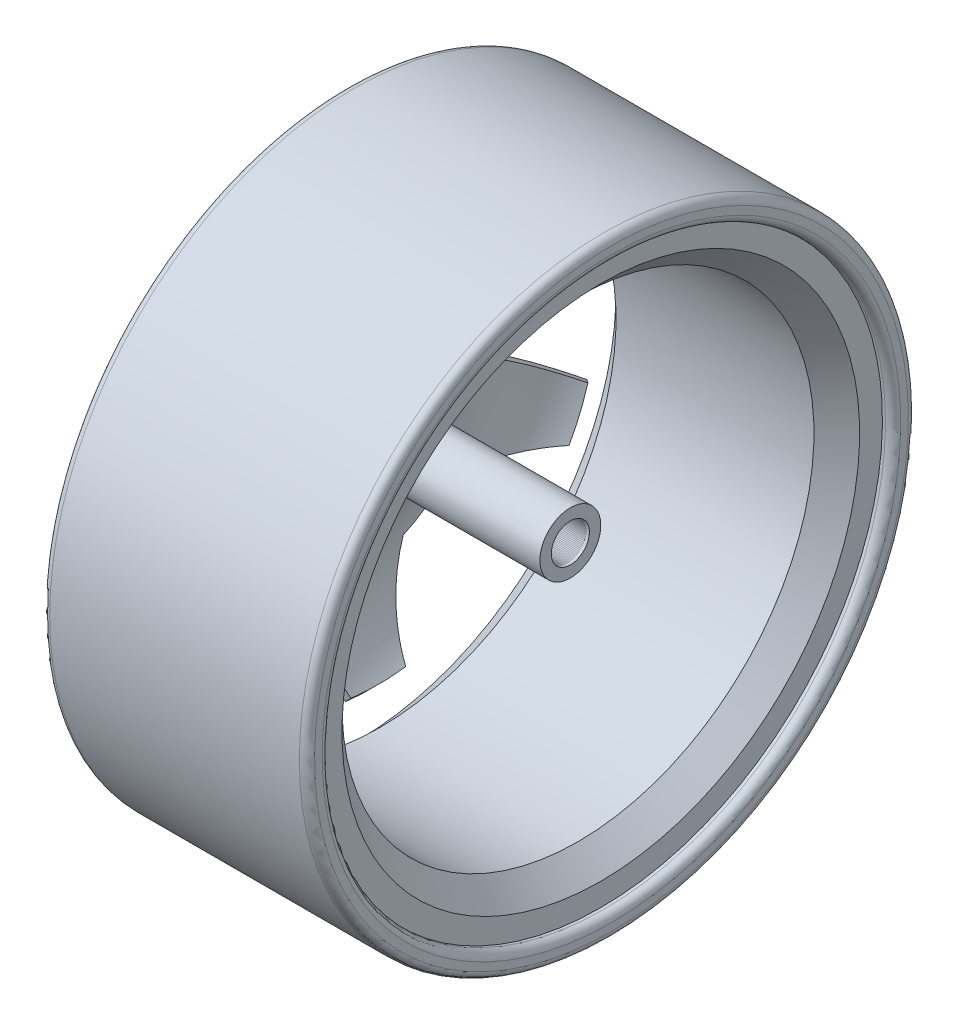
SolidWorks part; units mm, degrees
ref_plane "Front Plane" through (0, 0, 0) normal (0, 0, 1) x (1, 0, 0)
ref_plane "Top Plane" through (0, 0, 0) normal (0, 1, 0) x (1, 0, 0)
ref_plane "Right Plane" through (0, 0, 0) normal (1, 0, 0) x (0, 0, -1)
sketch "Sketch1" plane through (0, 0, 0) normal (0, 0, 1) x (1, 0, 0)
  line L0 (-5, 0) -> (5, 0) construction
  line L1 (0, 0) -> (0, 15.5) construction
  line L2 (-6.5, 15.5) -> (0, 15.5)
  line L3 (0, 15.5) -> (6.5, 15.5)
  line L4 (0, 0) -> (0, 18.5) construction
  line L5 (-6.5, 18.5) -> (6.5, 18.5) construction
  line L6 (0, 16.5) -> (-5, 16.5)
  line L7 (0, 16.5) -> (5, 16.5)
  line L8 (-6.5, 18.5) -> (-8, 18.5)
  line L9 (6.5, 18.5) -> (8, 18.5)
  line L10 (-8, 18.5) -> (-8, 17)
  line L11 (8, 18.5) -> (8, 17)
  line L12 (-6.5, 18.5) -> (-5, 16.5)
  line L13 (-8, 17) -> (-6.5, 15.5)
  line L14 (6.5, 18.5) -> (5, 16.5)
  line L15 (8, 17) -> (6.5, 15.5)
  point P3 (0, 0)
  point P13 (0, 0)
  dimension "D1" = 15.5
  dimension "D2" = 6.5
  dimension "D3" = 18.5
  dimension "D4" = 1
  dimension "D5" = 5
  dimension "D6" = 5
  dimension "D7" = 1.5
  dimension "D8" = 1.5
  dimension "D9" = 1.5
  dimension "D10" = 1.5
  dimension "D11" = 10
revolve "Revolve1" add sketch "Sketch1" angle 360 about L0
sketch "Sketch2" plane through (0, 0, 0) normal (0, 0, 1) x (1, 0, 0)
  line L0 (-6, 2.5) -> (-4.5, 2.5)
  line L1 (-4.5, 2.5) -> (-4.5, 1.25)
  line L2 (-4.5, 1.25) -> (-3.75, 1.25)
  line L3 (-3.75, 1.25) -> (-3.75, 2.5)
  line L4 (-3.75, 2.5) -> (6, 2.5)
  line L5 (-5, 0) -> (5, 0) construction
  line L6 (-6, 2.5) -> (-6, 4.5)
  line L8 (-5.25, 4.5) -> (-5.25, 3.25)
  line L9 (-5.25, 3.25) -> (6, 3.25)
  line L10 (6, 3.25) -> (6, 2.5)
  line L11 (-8, 17) -> (-6.5, 15.5) construction
  line L12 (-6.6086, 15.6086) -> (-7.1389, 16.1389)
  arc A0 (-5.25, 4.5) -> (-6.6086, 15.6086) centre (-0.3145, 10.741) cw
  arc A1 (-6, 4.5) -> (-7.1389, 16.1389) centre (-0.9445, 10.8699) cw
  point P3 (-4.5, 2.5)
  point P5 (-3.75, 2.5)
  dimension "D1" = 12
  dimension "D2" = 1.25
  dimension "D3" = 2.5
  dimension "D4" = 1.5
  dimension "D5" = 0.75
  dimension "D6" = 2
  dimension "D7" = 0.75
  dimension "D8" = 0.75
  dimension "D9" = 0.75
revolve "Revolve2" add sketch "Sketch2" angle 360 about L2
sketch "Sketch6" plane through (0, 0, 0) normal (1, 0, 0) x (0, 0, -1)
  line L0 (0, 1.25) -> (0, 7.8126) construction
  line L1 (8.4749, 13.4916) -> (1.5, 7.6389)
  line L2 (-1.5, 7.6389) -> (-8.4749, 13.4916)
  line L3 (15.4501, -3.891) -> (7.7286, 0.934)
  line L4 (6.8015, 3.7871) -> (10.2123, 12.2292)
  line L5 (1.0738, -15.8963) -> (3.2765, -7.0617)
  line L6 (5.7036, -5.2983) -> (14.7865, -5.9335)
  line L7 (-14.7865, -5.9335) -> (-5.7036, -5.2983)
  line L8 (-3.2765, -7.0617) -> (-1.0738, -15.8963)
  line L9 (-10.2123, 12.2292) -> (-6.8015, 3.7871)
  line L10 (-7.7286, 0.934) -> (-15.4501, -3.891)
  arc A0 (1.2622, -15.1405) -> (14.7865, -5.9335) centre (0, 1.25) ccw
  arc A2 (1.5, 7.6389) -> (-1.5, 7.6389) centre (0, 1.25) ccw
  arc A3 (7.7286, 0.934) -> (6.8015, 3.7871) centre (1.1888, 0.3863) ccw
  arc A4 (3.2765, -7.0617) -> (5.7036, -5.2983) centre (0.7347, -1.0113) ccw
  arc A5 (-5.7036, -5.2983) -> (-3.2765, -7.0617) centre (-0.7347, -1.0113) ccw
  arc A6 (-6.8015, 3.7871) -> (-7.7286, 0.934) centre (-1.1888, 0.3863) ccw
  arc A7 (14.2304, -3.1289) -> (10.17, 12.1244) centre (0, 1.25) ccw
  arc A10 (8.4749, 13.4916) -> (-8.4749, 13.4916) centre (0, 1.25) ccw
  arc A11 (-14.7865, -5.9335) -> (-1.2622, -15.1405) centre (0, 1.25) ccw
  arc A12 (-10.17, 12.1244) -> (-14.2304, -3.1289) centre (0, 1.25) ccw
  point P31 (0, 0)
  dimension "D1" = 3
  dimension "D2" = 50
  dimension "D3" = 50
  dimension "D5" = 5
extrude "Cut-Extrude1" cut sketch "Sketch6" against normal blind 10 and the other way through all contours L1 A10 L2 A2 | L3 A7 L4 A3 | A4 L5 A0 L6 | L7 A11 L8 A5 | L9 A12 L10 A6
sketch "Sketch8" plane through (0, 0, 0) normal (0, 0, 1) x (1, 0, 0)
  line L0 (-8.2, 18.5) -> (-6.5, 18.5)
  line L1 (-6.5, 18.5) -> (-8, 18.5) construction
  line L2 (-6.5, 18.5) -> (-5, 16.5)
  line L3 (-5, 16.5) -> (5, 16.5)
  line L4 (5, 16.5) -> (6.5, 18.5)
  line L5 (6.5, 18.5) -> (8.2, 18.5)
  line L6 (6.5, 18.5) -> (8, 18.5) construction
  line L7 (8.7, 19) -> (8.7, 19.5)
  line L8 (8.2, 20) -> (-8.2, 20)
  line L9 (-8.7, 19.5) -> (-8.7, 19)
  line L10 (-6.5, -18.5) -> (-6.5, 18.5) construction
  arc A0 (8.7, 19.5) -> (8.2, 20) centre (8.2, 19.5) ccw
  arc A1 (8.2, 18.5) -> (8.7, 19) centre (8.2, 19) ccw
  arc A2 (-8.2, 18.5) -> (-8.7, 19) centre (-8.2, 19) cw
  arc A3 (-8.2, 20) -> (-8.7, 19.5) centre (-8.2, 19.5) ccw
  point P5 (0, 20)
  point P24 (8.7, 18.5)
  point P27 (-8.7, 18.5)
  dimension "D3" = 0.5
  dimension "D1" = 20
  dimension "D2" = 2.2
revolve "Revolve3" add sketch "Sketch8" angle 360 about L0
fillet "Fillet1" radius 0.5 3 edges at (-6, 1.25, 1.25) (-4.5, 1.25, 1.25) (-6, 1.25, 3.25)
fillet "Fillet2" radius 0.1 20 edges at (-8.5499, -1.8095, 12.1191) (-7.1389, -4.5, 13.7338) (-8.6561, -5.6053, 10.0937) (-9.0332, -5.8327, 5.1869) (-8.5165, -11.1311, 2.2619) (-7.1389, -13.6389, 0) (-8.6665, -10.6868, -2.3727) (-9.0451, -6.7043, -3.9993) (-8.8314, -5.5565, -9.3962) (-7.1389, -4.5, -13.7338) (-8.9724, -0.9227, -10.6999) (-8.816, 2.0646, -7.5332) (-8.5628, 9.6798, -9.1823) (-7.1389, 12.839, -9.3475) (-8.4802, 7.8126, 0) (-9.0731, 10.076, 4.4045) (-7.1389, 12.839, 9.3475) (-8.9301, 8.3187, 8.6324) (-8.7801, 2.8611, 7.2669) (-9.0758, 9.8165, -4.0951)
sketch "Sketch9" plane through (6, 0, 0) normal (1, 0, 0) x (0, 0, -1)
  circle A0 centre (0, 1.25) radius 1.25 construction
  circle A1 centre (0, 1.25) radius 1.25
  circle A2 centre (0, 1.25) radius 1.5
  dimension "D1" = 3
extrude "Boss-Extrude1" add sketch "Sketch9" against normal blind 10 from offset 0.2 separate body offset against normal yes
equation "\"R15.50\"=36.38"
